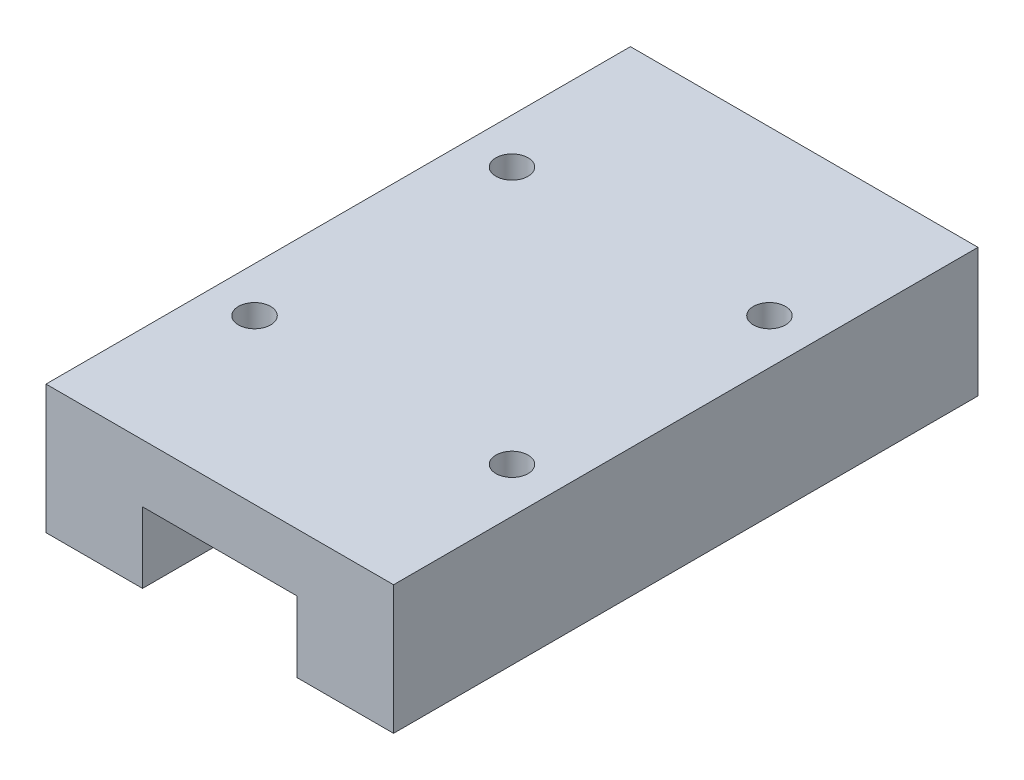
SolidWorks part; units mm, degrees
ref_plane "Front Plane" through (0, 0, 0) normal (0, 0, 1) x (1, 0, 0)
ref_plane "Top Plane" through (0, 0, 0) normal (0, 1, 0) x (1, 0, 0)
ref_plane "Right Plane" through (0, 0, 0) normal (1, 0, 0) x (0, 0, -1)
sketch "Sketch1" plane through (0, 0, 0) normal (0, 0, 1) x (1, 0, 0)
  line L0 (-13.5, 2.5069) -> (-6, 2.5069)
  line L1 (-6, 2.5069) -> (-6, 8)
  line L2 (-6, 8) -> (6, 8)
  line L3 (6, 8) -> (6, 2.5069)
  line L4 (6, 2.5069) -> (13.5, 2.5069)
  line L5 (13.5, 2.5069) -> (13.5, 12.5069)
  line L6 (13.5, 12.5069) -> (-13.5, 12.5069)
  line L7 (-13.5, 12.5069) -> (-13.5, 2.5069)
  dimension "D1" = 27
  dimension "D2" = 10
  dimension "D3" = 12
  dimension "D4" = 7.5
  dimension "D5" = 8
  dimension "D6" = 6
extrude "Boss-Extrude1" add sketch "Sketch1" along normal mid plane 45.4
sketch "Sketch2" plane through (0, 12.5069, 0) normal (0, 1, 0) x (1, 0, 0)
  line L1 (10, 10) -> (-10, 10) construction
  line L2 (10, 10) -> (10, -10) construction
  line L3 (10, -10) -> (-10, -10) construction
  line L4 (-10, 10) -> (-10, -10) construction
  line L5 (10, 10) -> (-10, -10) construction
  line L6 (10, -10) -> (-10, 10) construction
  circle A0 centre (-10, 10) radius 1.25
  circle A1 centre (10, 10) radius 1.25
  circle A2 centre (-10, -10) radius 1.25
  circle A3 centre (10, -10) radius 1.25
  point P0 (0, 0)
  point P7 (-10, 10)
  point P8 (10, 10)
  point P9 (10, -10)
  point P10 (-10, -10)
  dimension "D3" = 2.5
  dimension "D4" = 2.5
  dimension "D5" = 2.5
  dimension "D6" = 2.5
  dimension "D1" = 20
  dimension "D2" = 20
extrude "Cut-Extrude1" cut sketch "Sketch2" against normal blind 3.5
